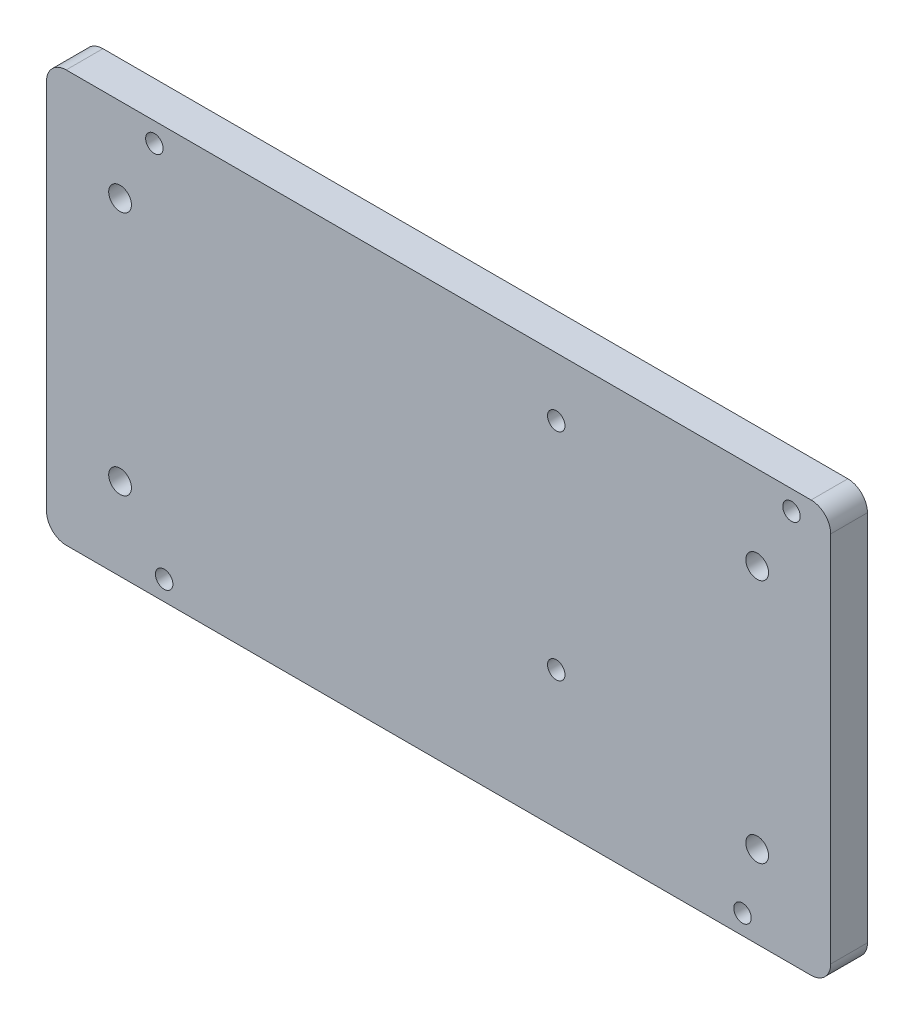
SolidWorks part; units mm, degrees
ref_plane "Front Plane" through (0, 0, 0) normal (0, 0, 1) x (1, 0, 0)
ref_plane "Top Plane" through (0, 0, 0) normal (0, 1, 0) x (1, 0, 0)
ref_plane "Right Plane" through (0, 0, 0) normal (1, 0, 0) x (0, 0, -1)
sketch "Sketch1" plane through (0, 0, 0) normal (0, 0, 1) x (1, 0, 0)
  line L1 (0, 0) -> (101.6, 0)
  line L2 (0, 0) -> (0, 53.34)
  line L3 (0, 53.34) -> (101.6, 53.34)
  line L4 (101.6, 0) -> (101.6, 53.34)
  dimension "D1" = 101.6
  dimension "D2" = 53.34
extrude "Boss-Extrude1" add sketch "Sketch1" along normal blind 4.7625
fillet "Fillet1" radius 2.54 4 edges at (101.6, 0, 2.3813) (0, 0, 2.3813) (0, 53.34, 2.3813) (101.6, 53.34, 2.3813)
hole_wizard "Tap Drill for #4-40 Tap1" positions "Sketch2" profile "Sketch3" hole size "#4-40" standard "ANSI Inch" end condition through all
sketch "Sketch2" plane through (0, 0, 0) normal (0, 0, -1) x (-1, 0, 0)
  point P0 (-15.24, 2.54)
  point P3 (-90.17, 2.54)
  point P6 (-96.52, 50.8)
  point P9 (-66.04, 17.78)
  point P12 (-66.04, 45.72)
  point P15 (-13.97, 50.8)
sketch "Sketch3" plane through (15.24, 2.54, 0) normal (1, 0, 0) x (0, 1, 0)
  line L0 (0, 0) -> (0, 4.7625)
  line L1 (0, 4.7625) -> (1.1303, 4.7625)
  line L2 (1.1303, 4.7625) -> (1.1303, 0)
  line L5 (1.1303, 0) -> (0, 0)
  line L11 (0, -6.35) -> (0, 107.95) construction
  dimension "Thru Hole Dia." = 2.2606
  dimension "Thru Hole Depth" = 4.7625
hole_wizard "#4 Clearance Hole2" positions "Sketch4" profile "Sketch6" hole size "#4" standard "ANSI Inch" end condition through all
sketch "Sketch4" plane through (0, 0, 4.7625) normal (0, 0, 1) x (1, 0, 0)
  line L1 (2.54, 0) -> (99.06, 0) construction
  line L2 (0, 50.8) -> (0, 2.54) construction
  line L4 (101.6, 2.54) -> (101.6, 50.8) construction
  point P7 (9.525, 42.418)
  point P9 (9.525, 10.668)
  point P25 (92.075, 42.418)
  point P26 (92.075, 10.668)
  point P28 (0, 0)
  point P29 (0, 0)
  point P32 (0, 0)
  point P37 (0, 0)
  point P38 (0, 0)
  dimension "D1" = 31.75
  dimension "D2" = 10.668
  dimension "D4" = 9.525
  dimension "D5" = 9.525
  dimension "D3" = 2
sketch "Sketch6" plane through (9.525, 42.418, 4.7625) normal (1, 0, 0) x (0, -1, 0)
  line L0 (0, 0) -> (0, 4.7625)
  line L1 (0, 4.7625) -> (1.4732, 4.7625)
  line L2 (1.4732, 4.7625) -> (1.4732, 0)
  line L5 (1.4732, 0) -> (0, 0)
  line L11 (0, -6.35) -> (0, 107.95) construction
  dimension "Thru Hole Dia." = 2.9464
  dimension "Thru Hole Depth" = 4.7625
